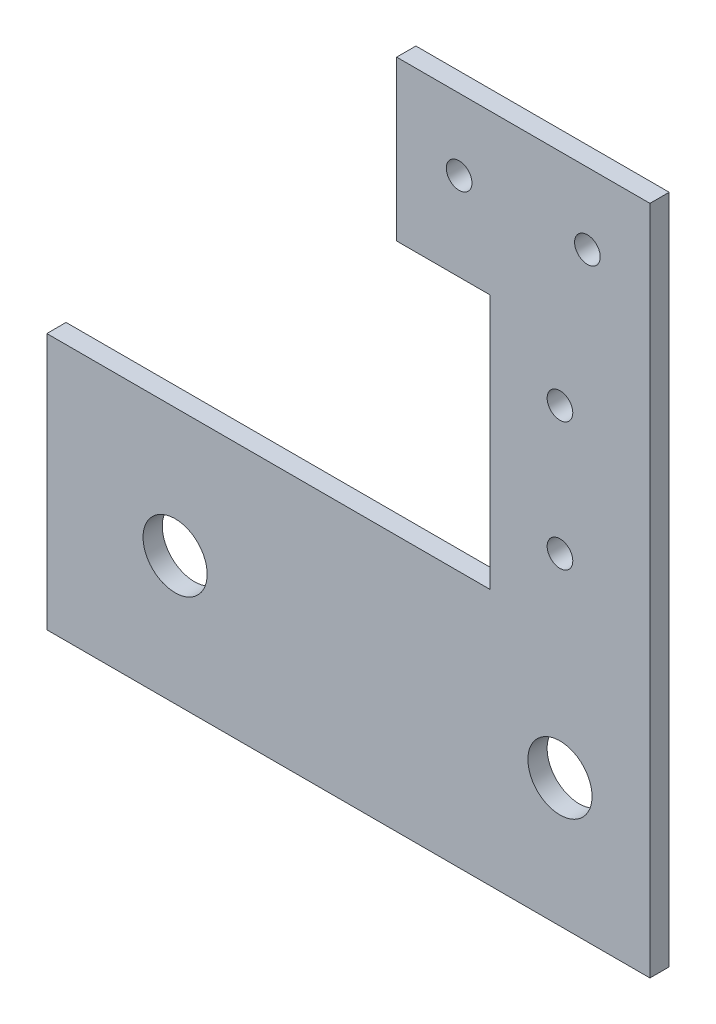
SolidWorks part; units mm, degrees
ref_plane "Front Plane" through (0, 0, 0) normal (0, 0, 1) x (1, 0, 0)
ref_plane "Top Plane" through (0, 0, 0) normal (0, 1, 0) x (1, 0, 0)
ref_plane "Right Plane" through (0, 0, 0) normal (1, 0, 0) x (0, 0, -1)
sketch "Sketch1" plane through (0, 0, 0) normal (0, 0, 1) x (1, 0, 0)
  line L2 (-12.4753, 19.6462) -> (-12.4753, -0.2335)
  line L3 (0, 32.0616) -> (0, 0)
  line L4 (-19.7437, 32.0616) -> (-19.7437, 19.6462)
  line L5 (0, -20.2335) -> (-47.0137, -20.2335)
  line L7 (0, 0) -> (0, -20.2335)
  line L8 (-12.4753, -20.2335) -> (-47.0137, -20.2335) construction
  line L9 (-19.7437, 19.6462) -> (-12.4753, 19.6462)
  line L10 (-47.0137, -0.2335) -> (-47.0137, -20.2335)
  line L14 (0.1263, 32.0616) -> (-19.7437, 32.0616)
  line L15 (-12.4753, -0.2335) -> (-47.0137, -0.2335)
  line L16 (-7.0137, -10.2335) -> (-37.0137, -10.2335)
  circle A0 centre (-7.0137, 4.9116) radius 0.9823
  circle A1 centre (-7.0137, 14.9116) radius 0.9823
  circle A6 centre (-14.8737, 26.5016) radius 1
  circle A7 centre (-4.8737, 26.5016) radius 1
  circle A8 centre (-7.0137, 14.9116) radius 1
  circle A9 centre (-7.0137, 4.9116) radius 1
  circle A10 centre (-37.0137, -10.2335) radius 2.5
  circle A11 centre (-7.0137, -10.2335) radius 2.5
  dimension "D2" = 20
  dimension "D4" = 5
  dimension "D8" = 1.9646
  dimension "D5" = 0.1263
  dimension "D10" = 2
  dimension "D1" = 10
  dimension "D3" = 7.0137
  dimension "D7" = 4.87
  dimension "D9" = 10
  dimension "D6" = 4.8737
  dimension "D11" = 12.4753
  dimension "D12" = 14.8737
  dimension "D13" = 37.0137
  dimension "D14" = 4.9116
  dimension "D15" = 19.6462
  dimension "D16" = 26.5016
  dimension "D17" = 32.0616
  dimension "D18" = 0.2335
  dimension "D19" = 10.2335
extrude "Boss-Extrude1" add sketch "Sketch1" along normal blind 1.5
